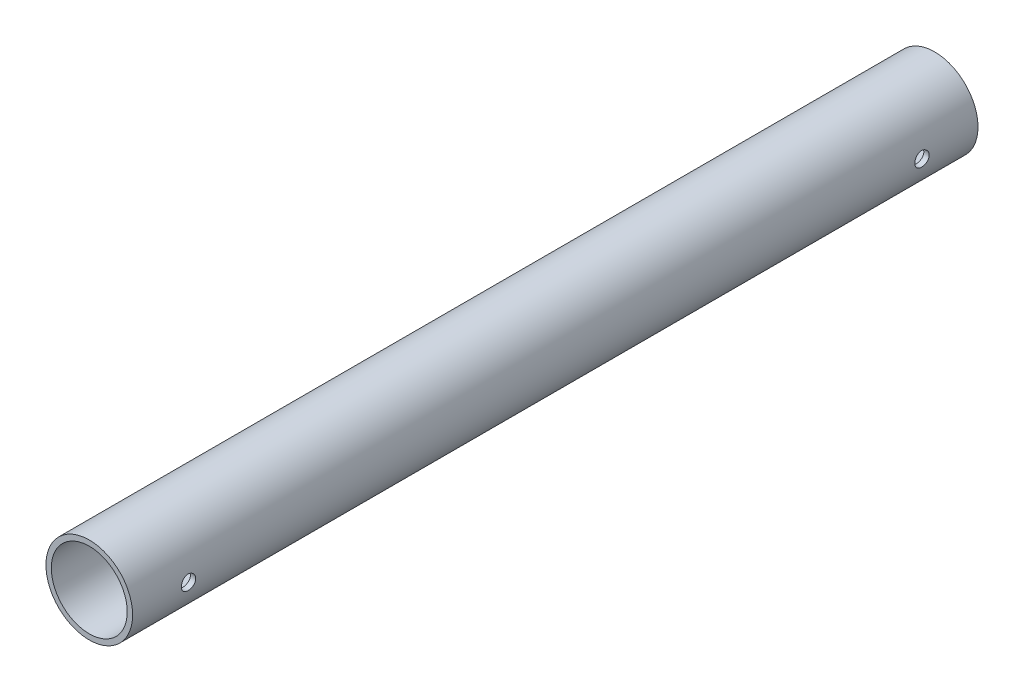
SolidWorks part; units mm, degrees
ref_plane "Front Plane" through (0, 0, 0) normal (0, 0, 1) x (1, 0, 0)
ref_plane "Top Plane" through (0, 0, 0) normal (0, 1, 0) x (1, 0, 0)
ref_plane "Right Plane" through (0, 0, 0) normal (1, 0, 0) x (0, 0, -1)
sketch "Sketch1" plane through (0, 0, 0) normal (0, 0, 1) x (1, 0, 0)
  circle A0 centre (0, 0) radius 12.1
  circle A1 centre (0, 0) radius 10.6
  dimension "D1" = 24.2
  dimension "D2" = 1.5
extrude "Boss-Extrude1" add sketch "Sketch1" along normal blind 118
sketch "Sketch2" plane through (0, 0, 0) normal (1, 0, 0) x (0, 0, -1)
  line L1 (-118, 12.1) -> (-118, -12.1) construction
  circle A1 centre (-102.375, 0) radius 2
  dimension "D1" = 4
  dimension "D2" = 15.625
extrude "Cut-Extrude1" cut sketch "Sketch2" against normal through all both and the other way through all
mirror "Mirror1" about plane through (0, 0, 0) normal (0, 0, 1) of "Boss-Extrude1", "Cut-Extrude1"
